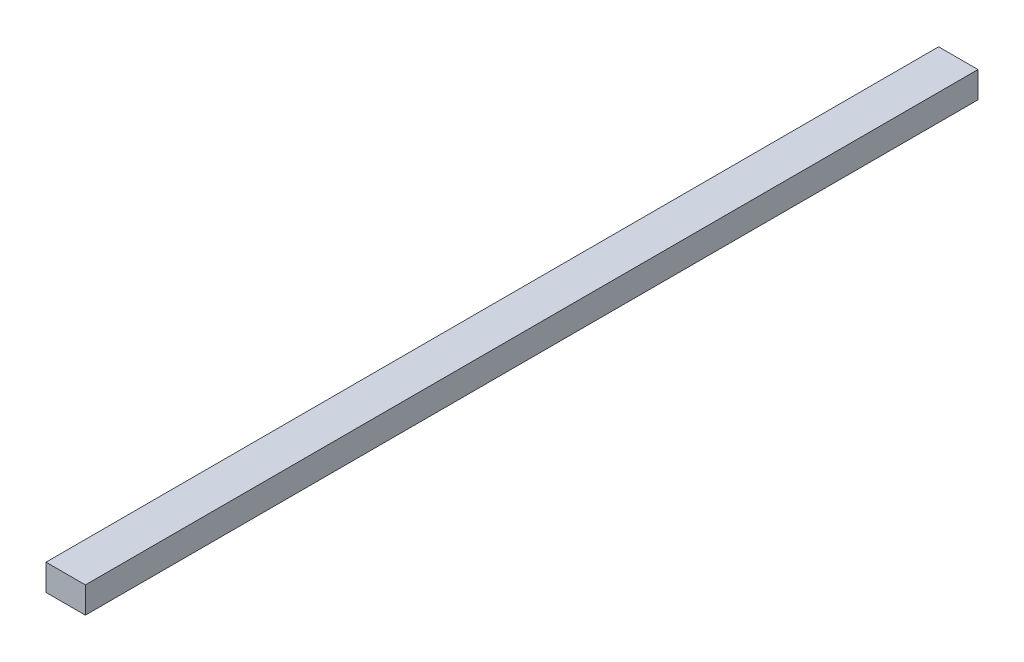
SolidWorks part; units mm, degrees
ref_plane "Front Plane" through (0, 0, 0) normal (0, 0, 1) x (1, 0, 0)
ref_plane "Top Plane" through (0, 0, 0) normal (0, 1, 0) x (1, 0, 0)
ref_plane "Right Plane" through (0, 0, 0) normal (1, 0, 0) x (0, 0, -1)
other "Configuration Table"
sketch "Sketch1" plane through (0, 0, 0) normal (0, 0, 1) x (1, 0, 0)
  line L1 (-65, 0) -> (-35, 0)
  line L2 (-65, 0) -> (-65, 20)
  line L3 (-65, 20) -> (-35, 20)
  line L4 (-35, 0) -> (-35, 20)
extrude "KAPYAG_kizak_sol_30x20_1" add sketch "Sketch1" against normal blind 680 from offset 20 separate body
